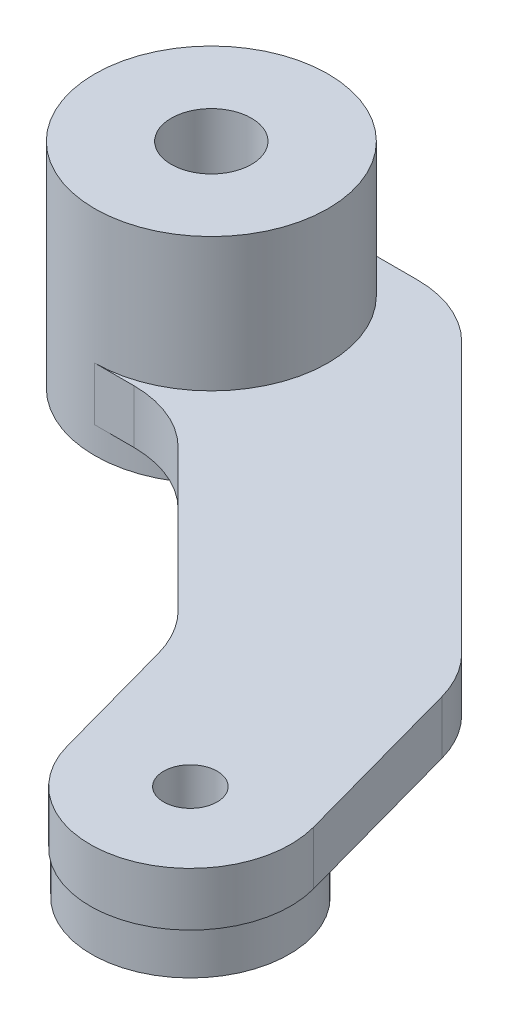
SolidWorks part; units mm, degrees
ref_plane "Front Plane" through (0, 0, 0) normal (0, 0, 1) x (1, 0, 0)
ref_plane "Top Plane" through (0, 0, 0) normal (0, 1, 0) x (1, 0, 0)
ref_plane "Right Plane" through (0, 0, 0) normal (1, 0, 0) x (0, 0, -1)
sketch "Sketch1" plane through (0, 0, 0) normal (0, 1, 0) x (1, 0, 0)
  line L0 (0, 4.3656) -> (3.3431, 4.3656)
  line L1 (6.1716, 3.1941) -> (16.2739, -6.9083)
  line L2 (17.3016, -8.6735) -> (19.1286, -15.2999)
  line L3 (0, -4.3656) -> (1.4678, -4.3656)
  line L4 (4.2962, -5.5372) -> (9.5701, -10.8111)
  line L5 (10.5978, -12.5763) -> (11.8984, -17.2934)
  circle A0 centre (0, 0) radius 1.5
  circle A1 centre (0, 0) radius 4.3656
  circle A2 centre (15.5135, -16.2967) radius 3.75
  circle A3 centre (15.5135, -16.2967) radius 1
  arc A4 (9.5701, -10.8111) -> (10.5978, -12.5763) centre (6.7417, -13.6395) cw
  arc A5 (16.2739, -6.9083) -> (17.3016, -8.6735) centre (13.4455, -9.7367) cw
  arc A6 (3.3431, 4.3656) -> (6.1716, 3.1941) centre (3.3431, 0.3656) cw
  arc A7 (4.2962, -5.5372) -> (1.4678, -4.3656) centre (1.4678, -8.3656) ccw
  point P13 (26.2194, -9.7905)
  point P16 (16.3263, -5.8066)
  point P17 (17.6542, -18.0237)
  point P18 (16.7108, -14.9044)
  point P19 (12.4089, -1.69)
  point P20 (15.5135, -16.2967)
  point P25 (17.0208, -7.6552)
  point P28 (5, 4.3656)
  dimension "D1" = 3
  dimension "D2" = 8.7312
  dimension "D3" = 2
  dimension "D4" = 7.5
  dimension "D10" = 4
  dimension "D5" = 7.5
  dimension "D6" = 5
  dimension "D7" = 22.5
  dimension "D8" = 17
  dimension "D9" = 135
extrude "Boss-Extrude1" add sketch "Sketch1" along normal blind 2 contours A7 L4 A4 L5 A2 L2 A5 L1 A6 L0 A1 L3 | A1 A0 | A2 A3
sketch "Sketch2" plane through (0, 0, 0) normal (0, -1, 0) x (1, 0, 0)
  line L0 (13.8238, 13.0079) -> (12.3516, 8.8322)
  line L1 (12.3516, 8.8322) -> (4.209, 0.8537)
  line L2 (4.209, 0.8537) -> (4.9088, 0.1394)
  line L3 (4.9088, 0.1394) -> (13.2175, 8.2806)
  line L4 (13.2175, 8.2806) -> (14.7669, 12.6754)
  line L5 (13.4737, 12.0148) -> (14.4168, 11.6823) construction
  line L6 (15.5135, 16.2967) -> (13.9452, 11.8485) construction
  line L7 (6.9332, 8.1741) -> (12.2365, 2.8708) construction
  line L8 (4.2962, 5.5372) -> (9.5701, 10.8111) construction
  line L9 (6.1716, -3.1941) -> (16.2739, 6.9083) construction
  line L10 (4.5589, 0.4966) -> (9.5848, 5.5225) construction
  circle A0 centre (15.5135, 16.2967) radius 1
  circle A1 centre (15.5135, 16.2967) radius 3.6974
  point P21 (0, 0)
  circle M23 centre (15.5135, 16.2967) radius 1
  dimension "D1" = 1
  dimension "D2" = 1
extrude "Boss-Extrude2" add sketch "Sketch2" along normal blind 1.5875 contours A1 L0 L1 L2 L3 L4 | A1 M23
sketch "Sketch3" plane through (9.1595, 0, -3.2293) normal (0.9431, 0, -0.3325) x (-0.3325, 0, -0.9431)
  line L0 (-16.8642, -1.5875) -> (-1.7637, 0)
  line L1 (-12.2043, -1.5875) -> (-16.8642, -1.5875) construction
  line L2 (-12.2043, -1.0976) -> (-1.7637, -1.0976)
  line L3 (-1.7637, -1.5875) -> (-1.7637, 0) construction
  line L4 (-1.7637, -1.0976) -> (-1.7637, -1.5875)
  line L5 (-1.7637, -1.5875) -> (-16.8642, -1.5875)
  line L6 (-16.8642, -1.5875) -> (-16.8642, 0) construction
  line L7 (-12.2043, -1.5875) -> (-12.2043, 0) construction
  point P13 (0, 0)
  line M3 (-16.8642, -1.5875) -> (-12.2043, -1.5875)
  line M4 (-12.2043, -1.5875) -> (-12.2043, 0)
extrude "Cut-Extrude1" cut sketch "Sketch3" against normal through all contours L5 L4 L2 M4 | L0 M3 M4
sketch "Sketch5" plane through (1.6349, 0, -1.6685) normal (-0.6999, 0, 0.7143) x (0.7143, 0, 0.6999)
  line L0 (15.0038, -1.122) -> (4.467, -0.0461)
  line L1 (3.5796, -1.1464) -> (3.5796, 0)
  line L2 (3.5796, -1.1464) -> (15.0038, -1.122)
  line L3 (3.0554, 0) -> (4.1038, 0) construction
  line L4 (3.8559, 0) -> (3.5796, 0)
  line L5 (15.0038, 0) -> (3.6038, 0) construction
  line L6 (-4.3656, 0) -> (3.0554, 0) construction
  spline S0 degree 3 poles (3.8559, 0) (4.033, 0) (4.2896, -0.028) (4.467, -0.0461) knots 0 0 0 0 1 1 1 1
  point P3 (3.1041, -0.0444)
  point P6 (4.0554, -0.0577)
  point P12 (3.6421, 0)
  point P13 (3.5721, 0)
  point P14 (4.2586, -0.0332)
  point P15 (4.467, -0.0461)
  point P16 (3.8559, 0)
  point P17 (3.5796, 0)
extrude "Cut-Extrude3" cut sketch "Sketch5" against normal through all
sketch "Sketch6" plane through (0, 0, 0) normal (0, -1, 0) x (1, 0, 0)
  circle A0 centre (0, 0) radius 1.5
  circle A1 centre (0, 0) radius 4.3656
extrude "Boss-Extrude3" add sketch "Sketch6" along normal blind 1
sketch "Sketch7" plane through (0, 2, 0) normal (0, 1, 0) x (1, 0, 0)
  circle A0 centre (0, 0) radius 1.5
  circle A1 centre (0, 0) radius 4.3656
  circle A2 centre (0, 0) radius 1.5 construction
extrude "Boss-Extrude4" add sketch "Sketch7" along normal blind 5
